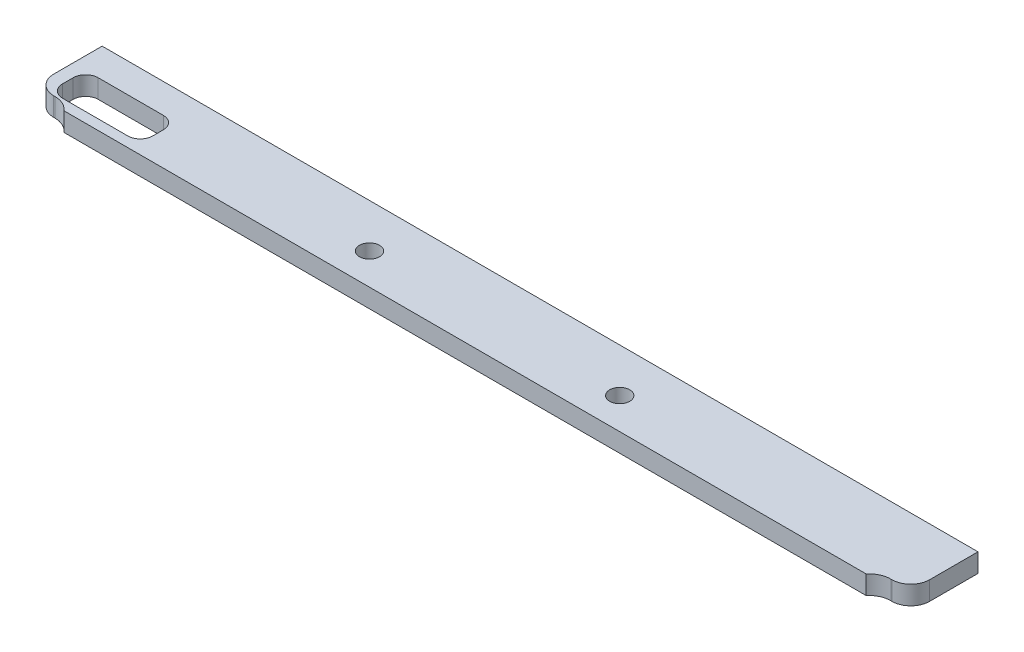
SolidWorks part; units mm, degrees
ref_plane "Front Plane" through (0, 0, 0) normal (0, 0, 1) x (1, 0, 0)
ref_plane "Top Plane" through (0, 0, 0) normal (0, 1, 0) x (1, 0, 0)
ref_plane "Right Plane" through (0, 0, 0) normal (1, 0, 0) x (0, 0, -1)
sketch "Sketch3" plane through (0, 0, 0) normal (0, 1, 0) x (1, 0, 0)
  line L6 (131.3747, -33.8347) -> (131.3747, -26.0938)
  line L7 (131.3747, -26.0938) -> (-8.6253, -26.0938)
  line L8 (-8.6253, -26.0938) -> (-8.6253, -33.8347)
  line L9 (-5.6253, -36.8347) -> (-5.431, -36.8347)
  line L10 (-2.7409, -38.0957) -> (125.4903, -38.0957)
  line L11 (128.1804, -36.8347) -> (128.3747, -36.8347)
  line L12 (131.3747, -33.8347) -> (131.3747, -26.0938)
  line L13 (131.3747, -26.0938) -> (-8.6253, -26.0938)
  line L14 (-8.6253, -26.0938) -> (-8.6253, -33.8347)
  line L15 (-5.6253, -36.8347) -> (-5.431, -36.8347)
  line L16 (-2.7409, -38.0957) -> (125.4903, -38.0957)
  line L17 (128.1804, -36.8347) -> (128.3747, -36.8347)
  arc A4 (-8.6253, -33.8347) -> (-5.6253, -36.8347) centre (-5.6253, -33.8347) ccw
  arc A5 (-2.7409, -38.0957) -> (-5.431, -36.8347) centre (-5.431, -40.3347) ccw
  arc A6 (128.1804, -36.8347) -> (125.4903, -38.0957) centre (128.1804, -40.3347) ccw
  arc A7 (128.3747, -36.8347) -> (131.3747, -33.8347) centre (128.3747, -33.8347) ccw
  arc A8 (-8.6253, -33.8347) -> (-5.6253, -36.8347) centre (-5.6253, -33.8347) ccw
  arc A9 (-2.7409, -38.0957) -> (-5.431, -36.8347) centre (-5.431, -40.3347) ccw
  arc A10 (128.1804, -36.8347) -> (125.4903, -38.0957) centre (128.1804, -40.3347) ccw
  arc A11 (128.3747, -36.8347) -> (131.3747, -33.8347) centre (128.3747, -33.8347) ccw
  dimension "D1" = 0
extrude "Boss-Extrude1" add sketch "Sketch3" along normal blind 3
sketch "Sketch4" plane through (0, 3, 0) normal (0, 1, 0) x (1, 0, 0)
  arc A0 (81.1098, -31.4969) -> (81.1098, -34.6969) centre (81.1098, -33.0969) ccw construction
  arc A1 (81.1098, -34.6969) -> (81.1098, -31.4969) centre (81.1098, -33.0969) ccw construction
  arc A2 (41.1098, -31.4969) -> (41.1098, -34.6969) centre (41.1098, -33.0969) ccw construction
  arc A3 (41.1098, -34.6969) -> (41.1098, -31.4969) centre (41.1098, -33.0969) ccw construction
  arc A12 (81.1098, -31.4969) -> (81.1098, -34.6969) centre (81.1098, -33.0969) ccw
  arc A13 (81.1098, -34.6969) -> (81.1098, -31.4969) centre (81.1098, -33.0969) ccw
  arc A14 (41.1098, -31.4969) -> (41.1098, -34.6969) centre (41.1098, -33.0969) ccw
  arc A15 (41.1098, -34.6969) -> (41.1098, -31.4969) centre (41.1098, -33.0969) ccw
extrude "Cut-Extrude1" cut sketch "Sketch4" against normal up to next
sketch "Sketch5" plane through (0, 0, 0) normal (0, -1, 0) x (1, 0, 0)
  text T0 "2"
extrude "Cut-Extrude2" cut sketch "Sketch5" against normal blind 1
sketch "Sketch6" plane through (0, 3, 0) normal (0, 1, 0) x (1, 0, 0)
  line L0 (-5.5658, -32.7856) -> (-5.5658, -34.4774) construction
  line L2 (-4.5658, -35.4774) -> (5.8521, -35.4774) construction
  line L3 (6.8521, -34.4774) -> (6.8521, -32.7856) construction
  line L4 (5.8521, -31.7856) -> (-4.5658, -31.7856) construction
  line L5 (-5.5658, -32.7856) -> (-5.5658, -34.4774) construction
  line L6 (-4.5658, -35.4774) -> (5.8521, -35.4774) construction
  line L7 (6.8521, -34.4774) -> (6.8521, -32.7856) construction
  line L8 (5.8521, -31.7856) -> (-4.5658, -31.7856) construction
  line L9 (5.8521, -30.7856) -> (-4.5658, -30.7856)
  line L10 (-6.5658, -32.7856) -> (-6.5658, -34.4774)
  line L11 (-4.5658, -36.4774) -> (5.8521, -36.4774)
  line L12 (7.8521, -34.4774) -> (7.8521, -32.7856)
  arc A0 (-4.5658, -31.7856) -> (-5.5658, -32.7856) centre (-4.5658, -32.7856) ccw construction
  arc A1 (-5.5658, -34.4774) -> (-4.5658, -35.4774) centre (-4.5658, -34.4774) ccw construction
  arc A2 (5.8521, -35.4774) -> (6.8521, -34.4774) centre (5.8521, -34.4774) ccw construction
  arc A3 (6.8521, -32.7856) -> (5.8521, -31.7856) centre (5.8521, -32.7856) ccw construction
  arc A4 (-4.5658, -31.7856) -> (-5.5658, -32.7856) centre (-4.5658, -32.7856) ccw construction
  arc A5 (-5.5658, -34.4774) -> (-4.5658, -35.4774) centre (-4.5658, -34.4774) ccw construction
  arc A6 (5.8521, -35.4774) -> (6.8521, -34.4774) centre (5.8521, -34.4774) ccw construction
  arc A7 (6.8521, -32.7856) -> (5.8521, -31.7856) centre (5.8521, -32.7856) ccw construction
  arc A8 (-4.5658, -30.7856) -> (-6.5658, -32.7856) centre (-4.5658, -32.7856) ccw
  arc A9 (-6.5658, -34.4774) -> (-4.5658, -36.4774) centre (-4.5658, -34.4774) ccw
  arc A10 (5.8521, -36.4774) -> (7.8521, -34.4774) centre (5.8521, -34.4774) ccw
  arc A11 (7.8521, -32.7856) -> (5.8521, -30.7856) centre (5.8521, -32.7856) ccw
  dimension "D1" = 1
extrude "Cut-Extrude3" cut sketch "Sketch6" against normal blind 3
